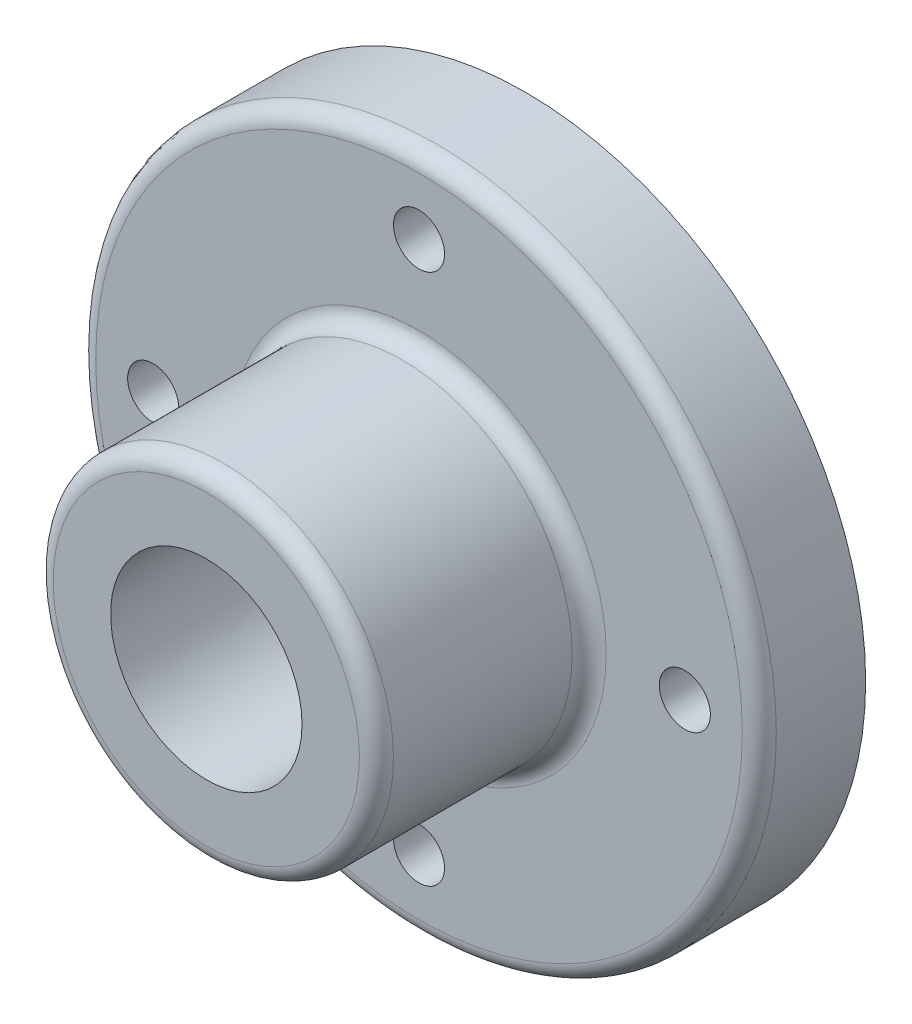
SolidWorks part; units mm, degrees
ref_plane "Plan de face" through (0, 0, 0) normal (0, 0, 1) x (1, 0, 0)
ref_plane "Plan de dessus" through (0, 0, 0) normal (0, 1, 0) x (1, 0, 0)
ref_plane "Plan de droite" through (0, 0, 0) normal (1, 0, 0) x (0, 0, -1)
sketch "Esquisse1" plane through (0, 0, 0) normal (0, 0, 1) x (1, 0, 0)
  circle A0 centre (0, 0) radius 80
  dimension "D1" = 160
extrude "Boss.-Extru.1" add sketch "Esquisse1" along normal blind 25 contours A0
sketch "Esquisse2" plane through (0, 0, 25) normal (0, 0, 1) x (1, 0, 0)
  circle A0 centre (0, 0) radius 40
  dimension "D1" = 80
extrude "Boss.-Extru.2" add sketch "Esquisse2" along normal blind 50 contours A0
sketch "Esquisse3" plane through (0, 0, 25) normal (0, 0, 1) x (1, 0, 0)
  line L0 (-80, 0) -> (80, 0) construction
  line L1 (0, 80) -> (0, -80) construction
  circle A0 centre (0, 0) radius 62.5 construction
  circle A1 centre (0, 0) radius 80 construction
  circle A2 centre (0, 62.5) radius 6
  circle A3 centre (62.5, 0) radius 6
  circle A4 centre (0, -62.5) radius 6
  circle A5 centre (-62.5, 0) radius 6
  dimension "D1" = 125
  dimension "D2" = 12
  dimension "D3" = 12
  dimension "D4" = 12
  dimension "D5" = 12
extrude "Enlèv. mat.-Extru.1" cut sketch "Esquisse3" against normal through all
sketch "Esquisse4" plane through (0, 0, 75) normal (0, 0, 1) x (1, 0, 0)
  circle A0 centre (0, 0) radius 22.5
  dimension "D1" = 45
extrude "Enlèv. mat.-Extru.2" cut sketch "Esquisse4" against normal through all contours A0
fillet "Congé1" radius 4 3 edges at (80, 0, 25) (40, 0, 25) (40, 0, 75)
